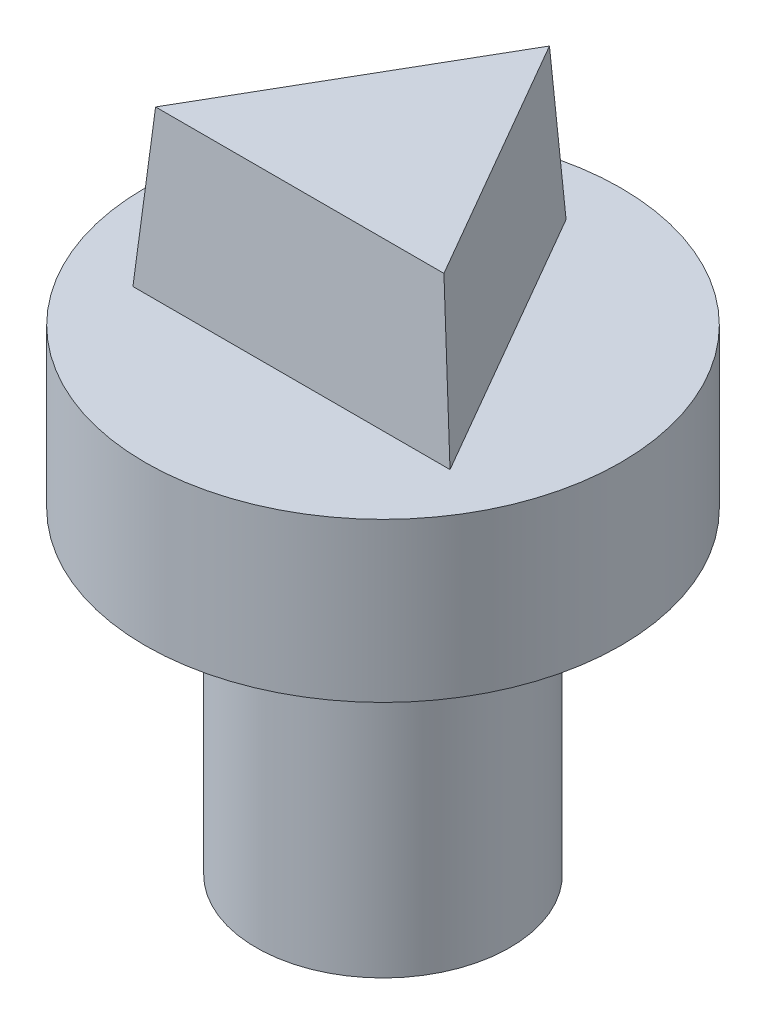
SolidWorks part; units mm, degrees
ref_plane "Front Plane" through (0, 0, 0) normal (0, 0, 1) x (1, 0, 0)
ref_plane "Top Plane" through (0, 0, 0) normal (0, 1, 0) x (1, 0, 0)
ref_plane "Right Plane" through (0, 0, 0) normal (1, 0, 0) x (0, 0, -1)
sketch "Sketch1" plane through (0, 0, 0) normal (0, 1, 0) x (1, 0, 0)
  circle A0 centre (0, 0) radius 7.5
  dimension "D1" = 15
extrude "Boss-Extrude1" add sketch "Sketch1" along normal blind 5
sketch "Sketch2" plane through (0, 5, 0) normal (0, 1, 0) x (1, 0, 0)
  line L1 (0, 5.7735) -> (-5, -2.8868)
  line L2 (-5, -2.8868) -> (5, -2.8868)
  line L3 (5, -2.8868) -> (0, 5.7735)
  circle A0 centre (0, 0) radius 2.8868 construction
  dimension "D1" = 10
extrude "Boss-Extrude2" add sketch "Sketch2" along normal blind 5 draft 3
sketch "Sketch3" plane through (0, 0, 0) normal (0, -1, 0) x (1, 0, 0)
  circle A0 centre (0, 0) radius 4
  dimension "D1" = 8
extrude "Boss-Extrude3" add sketch "Sketch3" along normal blind 10
equation "\"base_side\"= 15mm"
equation "\"base_thickness\"= 5mm"
equation "\"Connector_Dia\"= 8mm"
equation "\"Connector_height\"= 10mm"
equation "\"D1@Sketch1\"=\"base_side\""
equation "\"D1@Boss-Extrude1\"=\"base_thickness\""
equation "\"D1@Sketch3\"=\"Connector_Dia\""
equation "\"D1@Boss-Extrude3\"=\"Connector_height\""
equation "\"Indenter_height\"= 5mm"
equation "\"Indenter_sides\"= 10mm"
equation "\"Draft_angle\"= 0deg"
equation "\"D1@Boss-Extrude2\"=\"Indenter_height\""
equation "\"D1@Sketch2\"=\"Indenter_sides\""
equation "\"D3@Boss-Extrude2\"=\"Draft_angle\""
